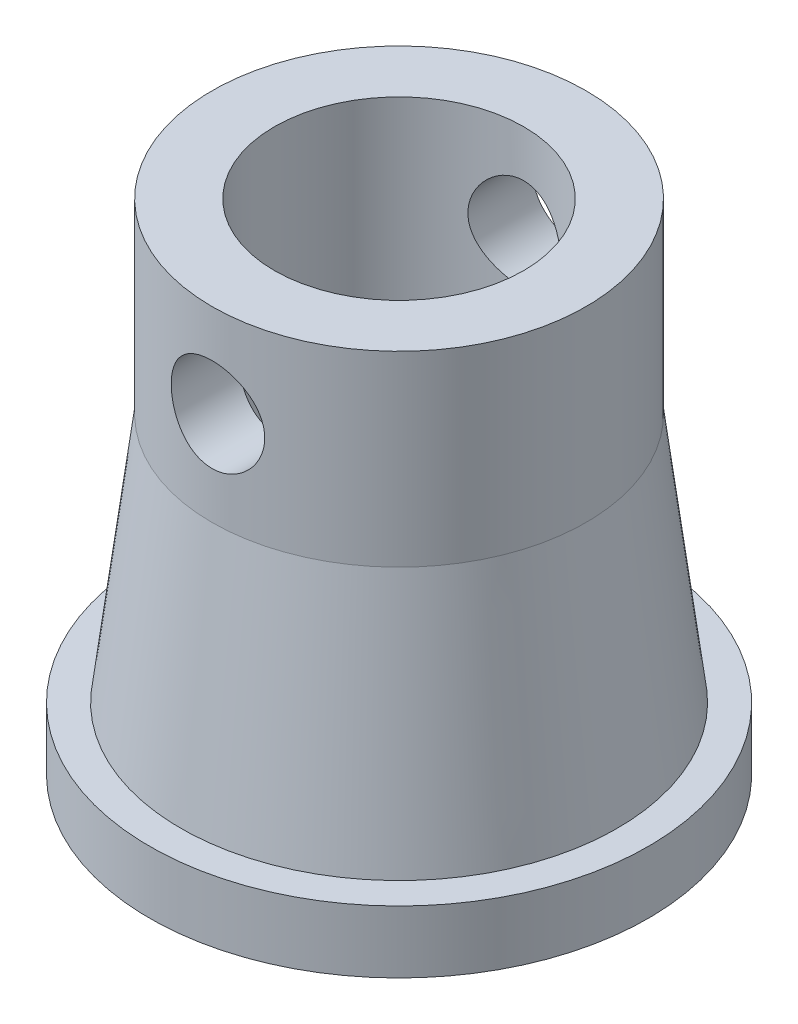
SolidWorks part; units mm, degrees
ref_plane "Front Plane" through (0, 0, 0) normal (0, 0, 1) x (1, 0, 0)
ref_plane "Top Plane" through (0, 0, 0) normal (0, 1, 0) x (1, 0, 0)
ref_plane "Right Plane" through (0, 0, 0) normal (1, 0, 0) x (0, 0, -1)
sketch "Sketch1" plane through (0, 0, 0) normal (0, 0, 1) x (1, 0, 0)
  line L0 (20, 0) -> (40, 0)
  line L1 (40, 0) -> (40, 10)
  line L2 (40, 10) -> (35, 10)
  line L3 (0, 0) -> (0, 80)
  line L4 (20, 80) -> (30, 80)
  line L5 (30, 80) -> (30, 50)
  line L6 (30, 50) -> (35, 10)
  line L7 (20, 0) -> (20, 80)
  dimension "D1" = 40
  dimension "D2" = 10
  dimension "D3" = 5
  dimension "D4" = 80
  dimension "D5" = 30
  dimension "D6" = 30
  dimension "D7" = 20
revolve "Revolve1" add sketch "Sketch1" angle 360 about L3
sketch "Sketch2" plane through (0, 0, 0) normal (0, 0, 1) x (1, 0, 0)
  circle A1 centre (0, 65) radius 7.5
  dimension "D2" = 15
extrude "Cut-Extrude1" cut sketch "Sketch2" against normal mid plane 70
